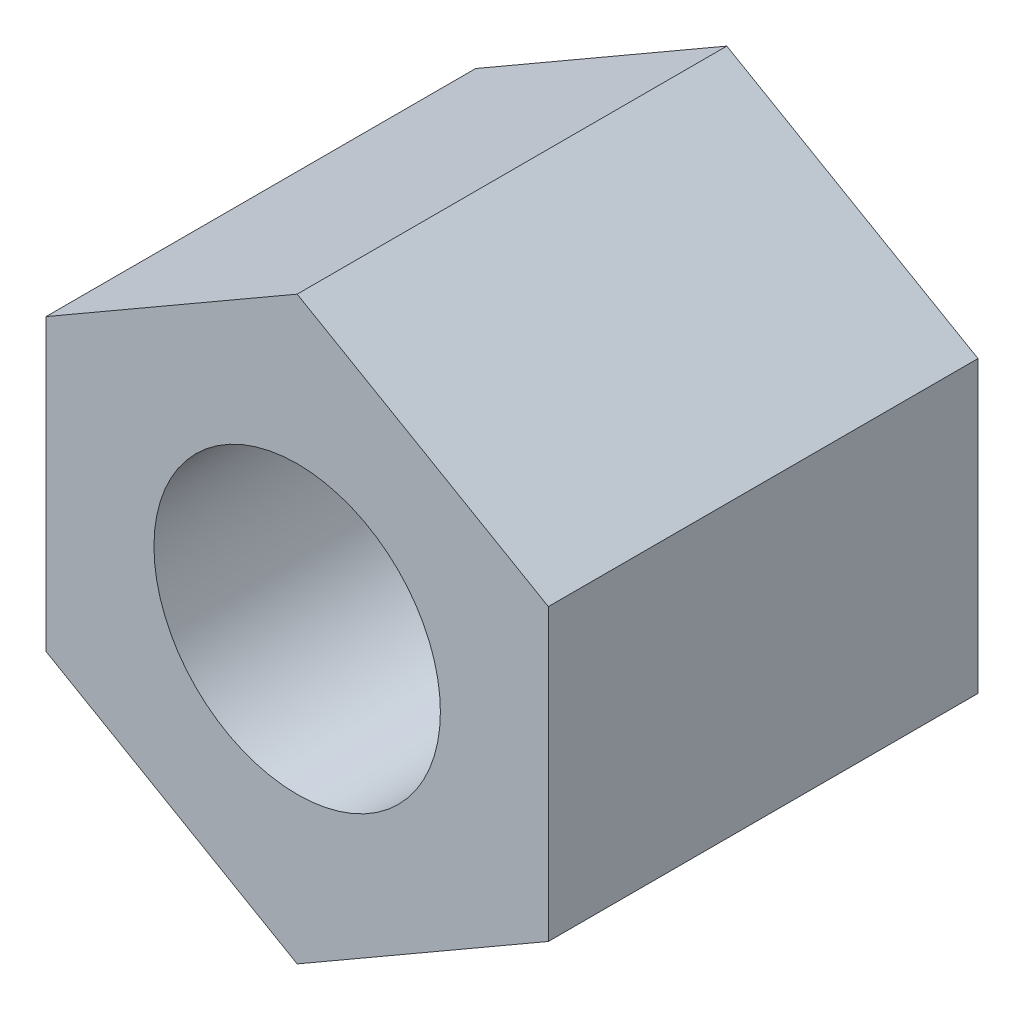
SolidWorks part; units mm, degrees
ref_plane "前视基准面" through (0, 0, 0) normal (0, 0, 1) x (1, 0, 0)
ref_plane "上视基准面" through (0, 0, 0) normal (0, 1, 0) x (1, 0, 0)
ref_plane "右视基准面" through (0, 0, 0) normal (1, 0, 0) x (0, 0, -1)
sketch "草图1" plane through (0, 0, 0) normal (0, 0, 1) x (1, 0, 0)
  line L0 (0, 0) -> (0, 4.05)
  line L1 (0, 4.05) -> (-3.5074, 2.025)
  line L2 (-3.5074, 2.025) -> (-3.5074, -2.025)
  line L3 (-3.5074, -2.025) -> (0, -4.05)
  line L4 (0, -4.05) -> (3.5074, -2.025)
  line L5 (3.5074, -2.025) -> (3.5074, 2.025)
  line L6 (3.5074, 2.025) -> (0, 4.05)
  circle A0 centre (0, 0) radius 3.5074 construction
  circle A1 centre (0, 0) radius 2
  dimension "D1" = 4
extrude "凸台-拉伸1" add sketch "草图1" along normal blind 6
